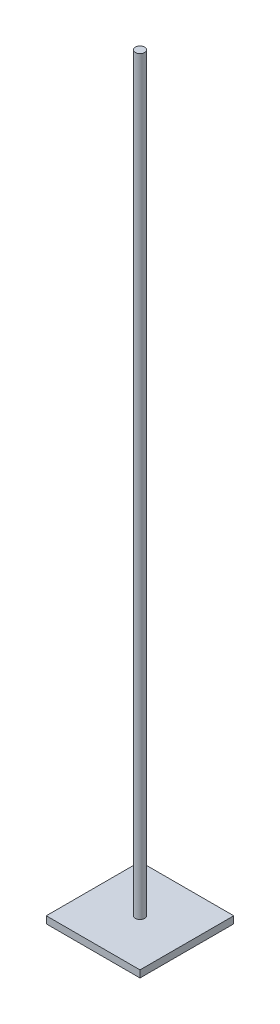
SolidWorks part; units mm, degrees
ref_plane "Front Plane" through (0, 0, 0) normal (0, 0, 1) x (1, 0, 0)
ref_plane "Top Plane" through (0, 0, 0) normal (0, 1, 0) x (1, 0, 0)
ref_plane "Right Plane" through (0, 0, 0) normal (1, 0, 0) x (0, 0, -1)
sketch "Sketch1" plane through (0, 0, 0) normal (0, 1, 0) x (1, 0, 0)
  line L1 (-100, -100) -> (100, -100)
  line L2 (-100, -100) -> (-100, 100)
  line L3 (-100, 100) -> (100, 100)
  line L4 (100, -100) -> (100, 100)
  line L5 (-100, -100) -> (100, 100) construction
  line L6 (-100, 100) -> (100, -100) construction
  point P0 (0, 0)
  dimension "D1" = 200
  dimension "D2" = 200
extrude "Boss-Extrude1" add sketch "Sketch1" along normal blind 15
sketch "Sketch2" plane through (0, 15, 0) normal (0, 1, 0) x (1, 0, 0)
  circle A0 centre (0, 0) radius 10
  dimension "D1" = 20
extrude "Boss-Extrude2" add sketch "Sketch2" along normal blind 1600
